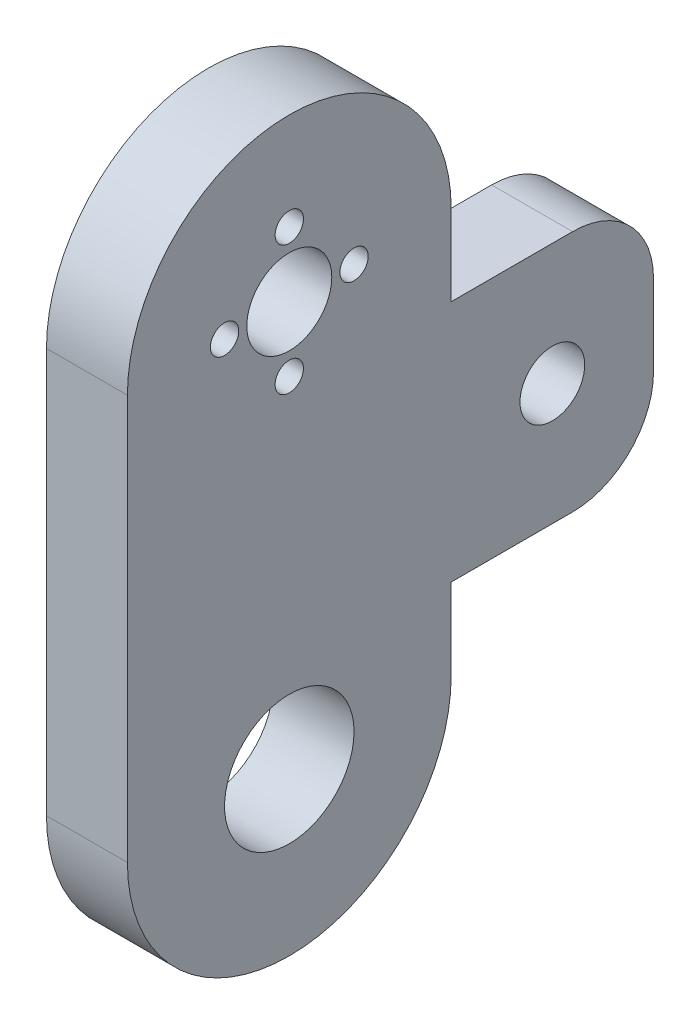
SolidWorks part; units mm, degrees
ref_plane "Alzado" through (0, 0, 0) normal (0, 0, 1) x (1, 0, 0)
ref_plane "Planta" through (0, 0, 0) normal (0, 1, 0) x (1, 0, 0)
ref_plane "Vista lateral" through (0, 0, 0) normal (1, 0, 0) x (0, 0, -1)
sketch "Croquis1" plane through (0, 0, 0) normal (1, 0, 0) x (0, 0, -1)
  line L0 (0, 45) -> (0, -45) construction
  line L1 (20, 15) -> (20, 25)
  line L2 (-20, -25) -> (-20, 25)
  line L3 (20, -15) -> (35, -15)
  line L4 (20, -25) -> (20, -15)
  line L5 (-20, -25) -> (20, 25) construction
  line L6 (-20, 25) -> (20, -25) construction
  line L7 (-20, 0) -> (45, 0) construction
  line L8 (20, 15) -> (35, 15)
  line L9 (45, -5) -> (45, 5)
  arc A0 (-20, -25) -> (20, -25) centre (0, -25) ccw
  circle A1 centre (0, 25) radius 5.25
  arc A2 (20, 25) -> (-20, 25) centre (0, 25) ccw
  circle A3 centre (0, -25) radius 8
  circle A4 centre (0, 33) radius 1.75
  circle A5 centre (8, 25) radius 1.75
  circle A6 centre (0, 17) radius 1.75
  circle A7 centre (-8, 25) radius 1.75
  circle A8 centre (32.5, 0) radius 4
  arc A9 (35, 15) -> (45, 5) centre (35, 5) cw
  arc A10 (35, -15) -> (45, -5) centre (35, -5) ccw
  point P0 (0, 0)
  point P23 (0, 25)
  point P31 (45, 15)
  point P34 (45, -15)
  dimension "D3" = 10.5
  dimension "D5" = 16
  dimension "D8" = 3.5
  dimension "D13" = 8
  dimension "D14" = 10
  dimension "D1" = 50
  dimension "D2" = 40
  dimension "D4" = 25
  dimension "D6" = 25
  dimension "D7" = 20
  dimension "D9" = 8
  dimension "D11" = 30
  dimension "D12" = 25
  dimension "D15" = 12.5
  dimension "D10" = 4
extrude "Saliente-Extruir1" add sketch "Croquis1" along normal blind 10
